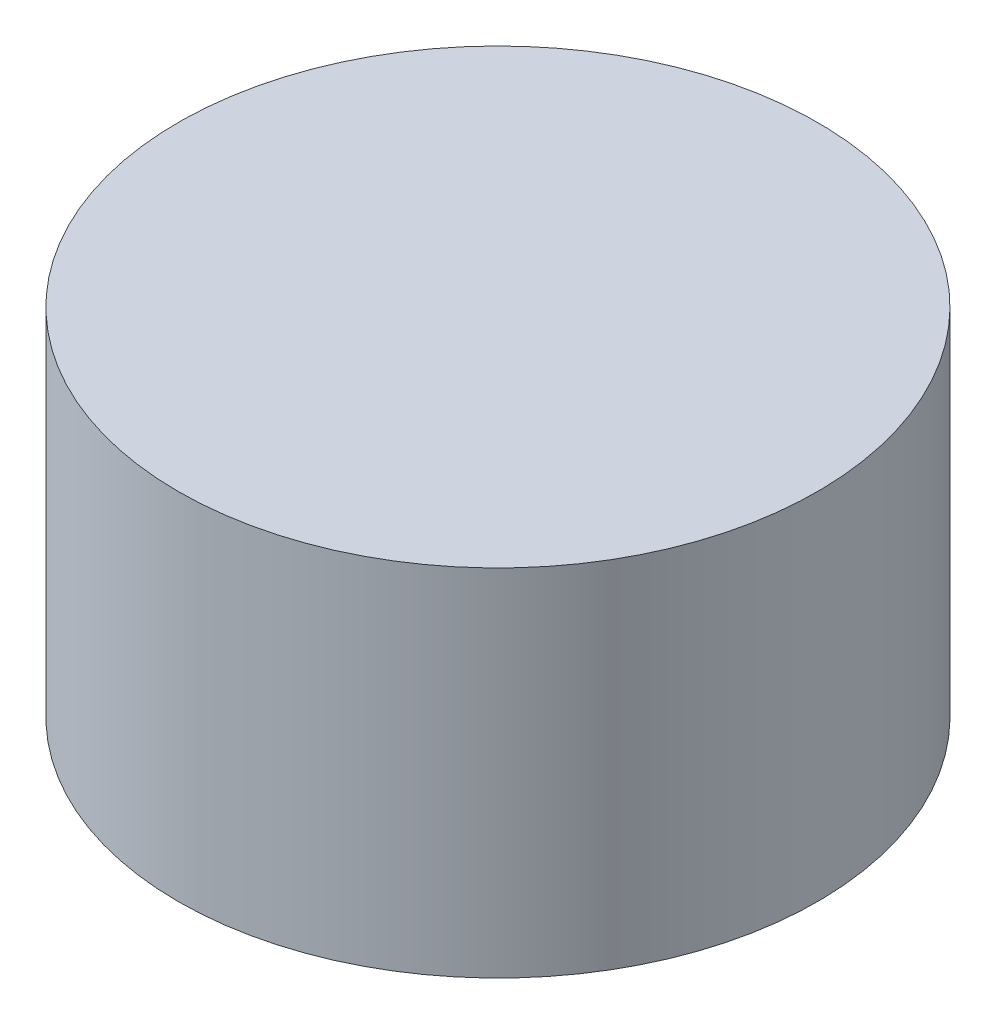
SolidWorks part; units mm, degrees
ref_plane "Front Plane" through (0, 0, 0) normal (0, 0, 1) x (1, 0, 0)
ref_plane "Top Plane" through (0, 0, 0) normal (0, 1, 0) x (1, 0, 0)
ref_plane "Right Plane" through (0, 0, 0) normal (1, 0, 0) x (0, 0, -1)
sketch "Sketch1" plane through (0, 0, 0) normal (0, 1, 0) x (1, 0, 0)
  circle A0 centre (0, 0) radius 90
  dimension "D1" = 180
extrude "Boss-Extrude1" add sketch "Sketch1" along normal blind 100
